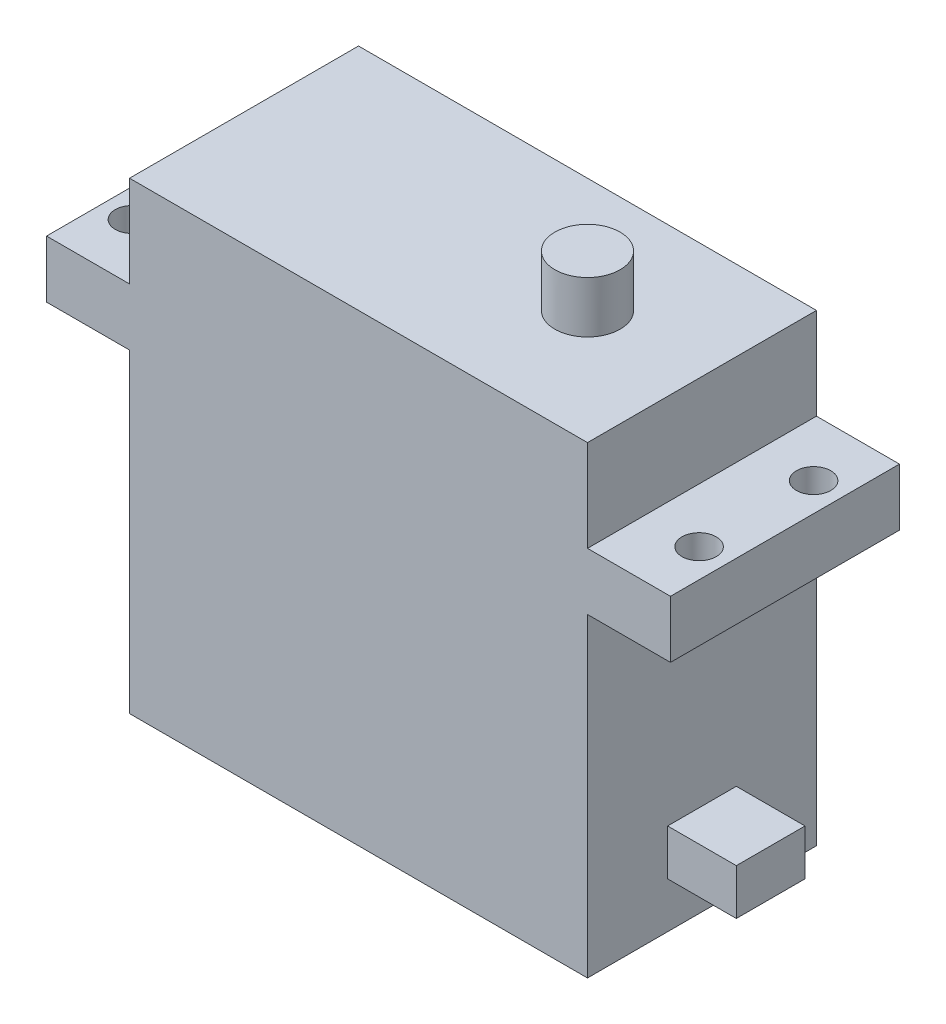
SolidWorks part; units mm, degrees
ref_plane "Front Plane" through (0, 0, 0) normal (0, 0, 1) x (1, 0, 0)
ref_plane "Top Plane" through (0, 0, 0) normal (0, 1, 0) x (1, 0, 0)
ref_plane "Right Plane" through (0, 0, 0) normal (1, 0, 0) x (0, 0, -1)
sketch "Sketch1" plane through (0, 0, 0) normal (0, 0, 1) x (1, 0, 0)
  line L0 (0, 0) -> (0, -23575.3117) construction
  line L2 (20, 0) -> (-20, 0)
  line L3 (20, 0) -> (20, -40.5)
  line L4 (20, -40.5) -> (-20, -40.5)
  line L5 (-20, 0) -> (-20, -40.5)
  line L6 (20, 0) -> (-20, -40.5) construction
  line L7 (20, -40.5) -> (-20, 0) construction
  line L8 (27.25, -13) -> (-27.25, -13)
  line L9 (27.25, -13) -> (27.25, -8)
  line L10 (27.25, -8) -> (-27.25, -8)
  line L11 (-27.25, -13) -> (-27.25, -8)
  line L12 (27.25, -13) -> (-27.25, -8) construction
  line L13 (27.25, -8) -> (-27.25, -13) construction
  point P3 (0, -20.25)
  point P8 (0, -10.5)
  point P14 (0, 0)
  dimension "D1" = 40
  dimension "D2" = 54.5
  dimension "D3" = 5
  dimension "D4" = 40.5
  dimension "D5" = 27.5
extrude "Boss-Extrude1" add sketch "Sketch1" along normal blind 20 contours L10 L3 L2 L5 | L11 L8 L5 L10 | L3 L10 L5 L8 | L9 L10 L3 L8 | L3 L8 L5 L4
sketch "Sketch2" plane through (0, 0, 0) normal (0, 1, 0) x (1, 0, 0)
  line L0 (20, 0) -> (-20, 0) construction
  line L1 (20, -20) -> (20, 0) construction
  circle A0 centre (10, -10) radius 2.85
  dimension "D1" = 10
  dimension "D2" = 10
  dimension "D3" = 5.7
extrude "Boss-Extrude2" add sketch "Sketch2" along normal blind 4.5
sketch "Sketch3" plane through (0, -8, 0) normal (0, 1, 0) x (1, 0, 0)
  line L0 (20, 0) -> (-20, 0) construction
  line L1 (-24.75, -15) -> (24.75, -15) construction
  line L2 (-24.75, -15) -> (-24.75, -5) construction
  line L3 (-24.75, -5) -> (24.75, -5) construction
  line L4 (24.75, -15) -> (24.75, -5) construction
  line L5 (-24.75, -15) -> (24.75, -5) construction
  line L6 (-24.75, -5) -> (24.75, -15) construction
  circle A0 centre (-24.75, -5) radius 1.5
  circle A1 centre (-24.75, -15) radius 1.5
  circle A2 centre (24.75, -15) radius 1.5
  circle A3 centre (24.75, -5) radius 1.5
  point P0 (0, -10)
  dimension "D4" = 3
  dimension "D1" = 10
  dimension "D2" = 10
  dimension "D3" = 49.5
extrude "Cut-Extrude1" cut sketch "Sketch3" against normal through all
sketch "Sketch4" plane through (20, 0, 0) normal (1, 0, 0) x (0, 0, -1)
  line L0 (-10, -40.5) -> (-10, -34.5) construction
  line L1 (-20, -40.5) -> (0, -40.5) construction
  line L3 (-13, -32.5) -> (-7, -32.5)
  line L4 (-13, -32.5) -> (-13, -36.5)
  line L5 (-13, -36.5) -> (-7, -36.5)
  line L6 (-7, -32.5) -> (-7, -36.5)
  line L7 (-13, -32.5) -> (-7, -36.5) construction
  line L8 (-13, -36.5) -> (-7, -32.5) construction
  dimension "D1" = 4
  dimension "D2" = 6
  dimension "D3" = 4
extrude "Boss-Extrude3" add sketch "Sketch4" along normal blind 6
